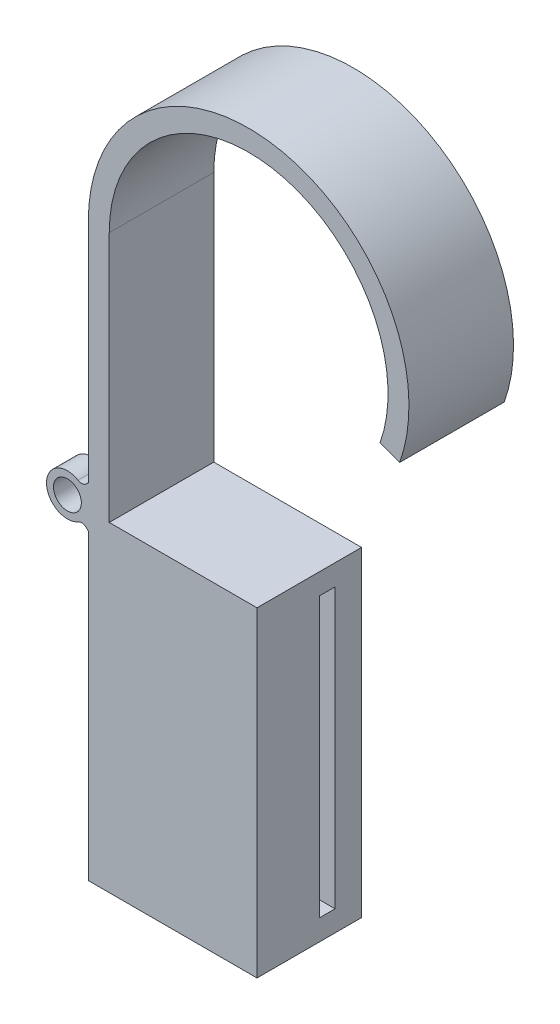
SolidWorks part; units mm, degrees
material "ABS"
ref_plane "Alzado" through (0, 0, 0) normal (0, 0, 1) x (1, 0, 0)
ref_plane "Planta" through (0, 0, 0) normal (0, 1, 0) x (1, 0, 0)
ref_plane "Vista lateral" through (0, 0, 0) normal (1, 0, 0) x (0, 0, -1)
sketch "Croquis1" plane through (0, 0, 0) normal (0, 0, 1) x (1, 0, 0)
  line L1 (0, 0) -> (10.6, 0)
  line L2 (0, 0) -> (0, 20)
  line L3 (0, 20) -> (10.6, 20)
  line L4 (10.6, 0) -> (10.6, 20)
  dimension "D1" = 10.6
  dimension "D2" = 20
extrude "Saliente-Extruir1" add sketch "Croquis1" along normal blind 1.5
sketch "Croquis22" plane through (0, 0, 1.5) normal (0, 0, 1) x (1, 0, 0)
  line L0 (0, -1.5) -> (12.1, -1.5)
  line L1 (12.1, -1.5) -> (12.1, 21.5)
  line L2 (0, 21.5) -> (12.1, 21.5)
  line L3 (0, 21.5) -> (0, 20)
  line L4 (0, 20) -> (10.6, 20)
  line L5 (0, -1.5) -> (0, 0)
  line L6 (0, 0) -> (10.6, 0)
  line L7 (10.6, 0) -> (10.6, 20)
  dimension "D1" = 1.5
  dimension "D2" = 1.5
  dimension "D3" = 1.5
extrude "Saliente-Extruir2" add sketch "Croquis22" against normal blind 7.5
sketch "Croquis23" plane through (10.6, 0, 0) normal (-1, 0, 0) x (0, 0, 1)
  line L0 (0, 0) -> (0, 20) construction
  line L1 (-4.1, 20) -> (-3, 20)
  line L2 (-4.1, 20) -> (-4.1, 0)
  line L3 (-4.1, 0) -> (-3, 0)
  line L4 (-3, 20) -> (-3, 0)
  line L5 (-6, 0) -> (0, 0) construction
  dimension "D1" = 1.1
  dimension "D2" = 20
  dimension "D3" = 3
  dimension "D4" = 0
extrude "Cortar-Extruir1" cut sketch "Croquis23" against normal through all
sketch "Croquis24" plane through (0, 0, -6) normal (0, 0, -1) x (-1, 0, 0)
  line L0 (-1.5, 21.5) -> (-1.5, 39.5)
  line L1 (-1.5, 21.5) -> (0, 21.5)
  line L3 (0, 21.5) -> (0, 39.5)
  line L4 (-20.9216, 36.1484) -> (-22.3349, 35.6457)
  arc A0 (-1.5, 39.5) -> (-20.9216, 36.1484) centre (-11.5, 39.5) ccw
  arc A1 (0, 39.5) -> (-22.3349, 35.6457) centre (-11.5, 39.5) ccw
  dimension "D1" = 10
  dimension "D2" = 11.5
  dimension "D3" = 18
extrude "Saliente-Extruir3" add sketch "Croquis24" against normal blind 7.5
sketch "Croquis25" plane through (0, 0, -6) normal (0, 0, -1) x (-1, 0, 0)
  line L0 (0, 39.5) -> (0, 20) construction
  line L1 (0, 20.2135) -> (0, 23.2135)
  line L2 (0, 23.2135) -> (0.1307, 23.0828)
  line L3 (0, 20.2135) -> (0.1307, 20.3442)
  arc A0 (0.7382, 20.4214) -> (0.7382, 23.0057) centre (1.5, 21.7135) ccw
  circle A1 centre (1.5, 21.7135) radius 1
  arc A2 (0.7382, 23.0057) -> (0.1307, 23.0828) centre (0.4842, 23.4364) cw
  arc A3 (0.7382, 20.4214) -> (0.1307, 20.3442) centre (0.4842, 19.9907) ccw
  dimension "D1" = 2
  dimension "D2" = 3
  dimension "D3" = 0.5
extrude "Saliente-Extruir5" add sketch "Croquis25" against normal blind 7.5
sketch "Croquis26" plane through (0, 20, 0) normal (0, -1, 0) x (1, 0, 0)
  line L0 (0, -6) -> (0, 0) construction
  line L1 (0, -0.25) -> (-6.0843, -0.25)
  line L2 (0, -0.25) -> (0, -4.25)
  line L3 (0, -4.25) -> (-6.0843, -4.25)
  line L4 (-6.0843, -0.25) -> (-6.0843, -4.25)
  line L5 (-0.1307, 1.5) -> (-0.7382, 1.5) construction
  line L6 (-3, -6) -> (-0.7382, -6) construction
  dimension "D1" = 1.75
  dimension "D2" = 1.75
extrude "Cortar-Extruir2" cut sketch "Croquis26" against normal blind 7.5
sketch "Croquis27" plane through (0, 0, 0) normal (-1, 0, 0) x (0, 0, 1)
  line L0 (-6, 39.5) -> (-6, 23.2135) construction
  line L1 (-2.75, 36.2704) -> (-1.75, 36.2704)
  line L2 (-2.75, 36.2704) -> (-2.75, 34.0704)
  line L3 (-2.75, 34.0704) -> (-1.75, 34.0704)
  line L4 (-1.75, 36.2704) -> (-1.75, 34.0704)
  line L5 (1.5, 39.5) -> (1.5, 23.2135) construction
  point P4 (-2.75, 35.1704)
  dimension "D1" = 3.25
  dimension "D2" = 3.25
  dimension "D3" = 2.2
extrude "Saliente-Extruir6" add sketch "Croquis27" along normal blind 3
fillet "Redondeo1" radius 1 2 edges at (-3, 36.2704, -2.25) (-3, 34.0704, -2.25)
sketch "Croquis28" plane through (0, 0, -1.75) normal (0, 0, 1) x (1, 0, 0)
  line L0 (0, 34.0704) -> (0, 36.2704) construction
  circle A0 centre (-2, 35.1704) radius 0.5
  dimension "D1" = 1
  dimension "D2" = 2
extrude "Cortar-Extruir3" cut sketch "Croquis28" against normal blind 5
